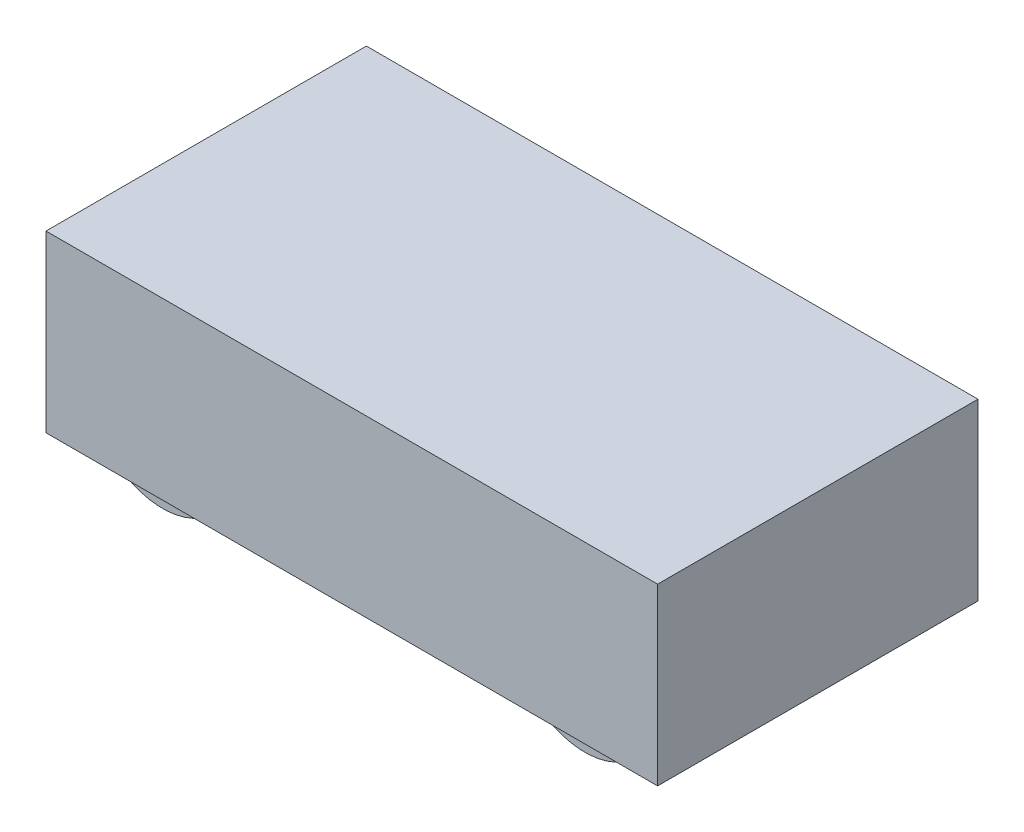
SolidWorks part; units mm, degrees
ref_plane "Front Plane" through (0, 0, 0) normal (0, 0, 1) x (1, 0, 0)
ref_plane "Top Plane" through (0, 0, 0) normal (0, 1, 0) x (1, 0, 0)
ref_plane "Right Plane" through (0, 0, 0) normal (1, 0, 0) x (0, 0, -1)
sketch "Chasis" plane through (0, 0, 0) normal (0, 1, 0) x (1, 0, 0)
  line L1 (-266.7, -139.7) -> (266.7, -139.7)
  line L2 (-266.7, -139.7) -> (-266.7, 139.7)
  line L3 (-266.7, 139.7) -> (266.7, 139.7)
  line L4 (266.7, -139.7) -> (266.7, 139.7)
  line L5 (-266.7, -139.7) -> (266.7, 139.7) construction
  line L6 (-266.7, 139.7) -> (266.7, -139.7) construction
  point P0 (0, 0)
  dimension "D1" = 533.4
  dimension "D2" = 279.4
extrude "Boss-Extrude1" add sketch "Chasis" along normal blind 152.4 contours L3 L4 L1 L2
ref_plane "Plane1" through (0, 38.1, 0) normal (0, -1, 0) x (-1, 0, 0)
sketch "Sketch3" plane through (0, 38.1, 0) normal (0, -1, 0) x (-1, 0, 0)
  line L0 (247.65, -69.85) -> (184.15, -69.85)
  line L1 (247.65, -69.85) -> (247.65, -120.65)
  line L2 (247.65, -120.65) -> (184.15, -120.65)
  line L3 (184.15, -69.85) -> (184.15, -120.65)
  line L4 (266.7, -139.7) -> (266.7, 139.7) construction
  line L5 (266.7, -139.7) -> (-266.7, -139.7) construction
  dimension "D1" = 63.5
  dimension "D2" = 50.8
  dimension "D3" = 19.05
  dimension "D4" = 19.05
revolve "Revolve2" add sketch "Sketch3" angle 360 about L3
mirror "Mirror1" about plane through (0, 0, 0) normal (0, 0, 1) of "Revolve2"
mirror "Mirror2" about plane through (0, 0, 0) normal (1, 0, 0) of "Mirror1", "Revolve2"
sketch "Sketch4" plane through (-266.7, 0, 0) normal (-1, 0, 0) x (0, 0, 1)
  line L0 (139.7, 152.4) -> (139.7, 0) construction
  line L1 (-50.8, 50.8) -> (50.8, 50.8)
  line L2 (-50.8, 50.8) -> (-50.8, 38.1)
  line L3 (-50.8, 38.1) -> (50.8, 38.1)
  line L4 (50.8, 50.8) -> (50.8, 38.1)
  line L6 (139.7, 0) -> (-139.7, 0) construction
  dimension "D1" = 101.6
  dimension "D2" = 88.9
  dimension "D3" = 50.8
  dimension "D4" = 12.7
extrude "Cut-Extrude1" cut sketch "Sketch4" against normal blind 241.3
